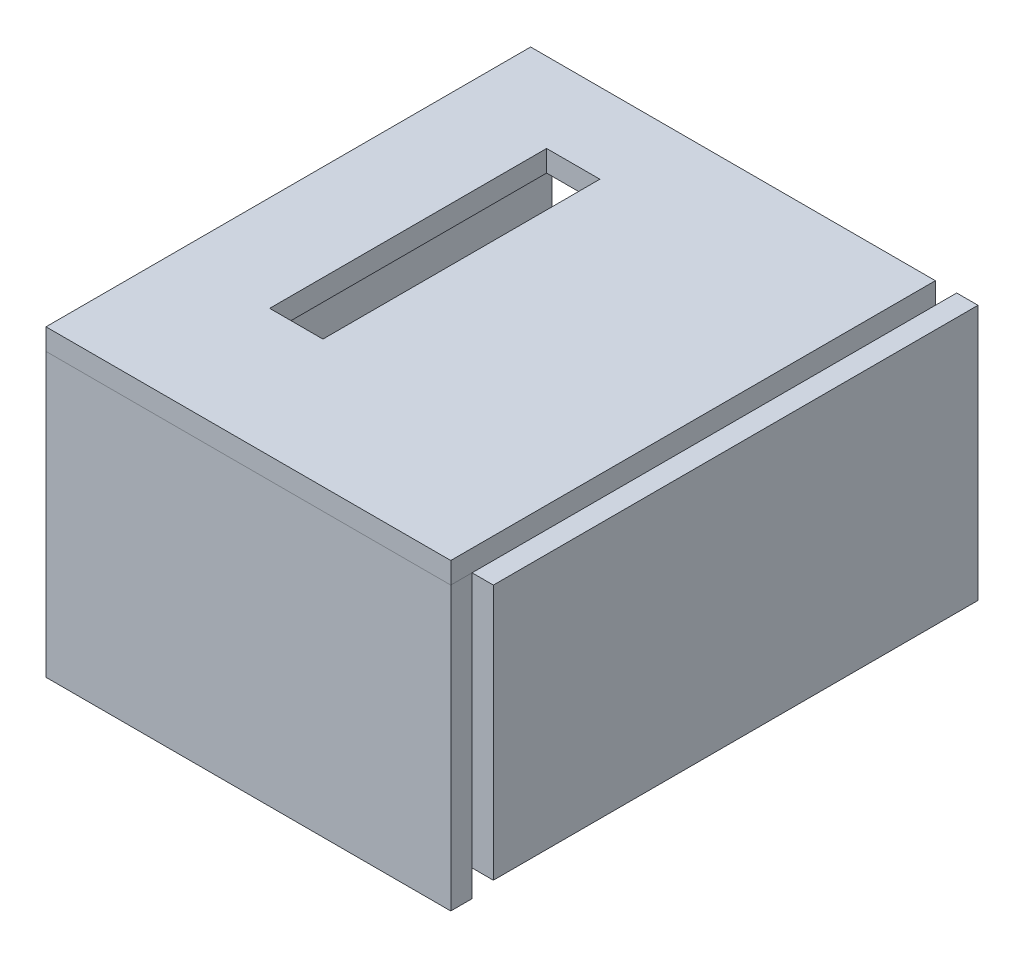
SolidWorks part; units mm, degrees
ref_plane "Front Plane" through (0, 0, 0) normal (0, 0, 1) x (1, 0, 0)
ref_plane "Top Plane" through (0, 0, 0) normal (0, 1, 0) x (1, 0, 0)
ref_plane "Right Plane" through (0, 0, 0) normal (1, 0, 0) x (0, 0, -1)
sketch "Sketch1" plane through (0, 0, 0) normal (0, 1, 0) x (1, 0, 0)
  line L0 (-120.65, -144.4625) -> (-120.65, -68.2625) construction
  line L1 (-120.65, 144.4625) -> (120.65, 144.4625)
  line L2 (-120.65, 144.4625) -> (-120.65, -144.4625)
  line L3 (-120.65, -144.4625) -> (120.65, -144.4625)
  line L4 (120.65, 144.4625) -> (120.65, -144.4625)
  line L5 (-120.65, 144.4625) -> (120.65, -144.4625) construction
  line L6 (-120.65, -144.4625) -> (120.65, 144.4625) construction
  line L7 (-120.65, -68.2625) -> (-63.5, -68.2625) construction
  line L8 (-63.5, -68.2625) -> (-31.75, -68.2625)
  line L9 (-63.5, -68.2625) -> (-63.5, 96.8375)
  line L10 (-63.5, 96.8375) -> (-31.75, 96.8375)
  line L11 (-31.75, 96.8375) -> (-31.75, -68.2625)
  point P0 (0, 0)
  dimension "D1" = 288.925
  dimension "D2" = 241.3
  dimension "D3" = 76.2
  dimension "D4" = 57.15
  dimension "D5" = 31.75
  dimension "D6" = 165.1
extrude "Boss-Extrude1" add sketch "Sketch1" along normal blind 12.7
sketch "Sketch2" plane through (0, 0, 144.4625) normal (0, 0, 1) x (1, 0, 0)
  line L0 (-120.65, 0) -> (120.65, 0)
  line L1 (-120.65, 0) -> (-120.65, -168.275)
  line L2 (120.65, 0) -> (120.65, -168.275)
  line L3 (-120.65, -168.275) -> (120.65, -168.275)
  dimension "D1" = 168.275
extrude "Boss-Extrude3" add sketch "Sketch2" against normal blind 12.7 separate body
sketch "Sketch3" plane through (120.65, 0, 0) normal (1, 0, 0) x (0, 0, -1)
  line L0 (-131.7625, 0) -> (157.1625, 0)
  line L1 (-131.7625, 0) -> (-131.7625, -152.4)
  line L2 (157.1625, 0) -> (157.1625, -152.4)
  line L3 (-131.7625, -152.4) -> (157.1625, -152.4)
  line L4 (-131.7625, -168.275) -> (-131.7625, 0) construction
  point P0 (157.8206, 0)
  dimension "D1" = 152.4
  dimension "D2" = 288.925
extrude "Boss-Extrude4" add sketch "Sketch3" along normal blind 12.7 separate body
sketch "Sketch5" plane through (-120.65, 0, 0) normal (-1, 0, 0) x (0, 0, 1)
  line L0 (-157.1625, 0) -> (131.7625, 0)
  line L1 (-157.1625, 0) -> (-157.1625, -152.4)
  line L2 (131.7625, 0) -> (131.7625, -152.4)
  line L3 (-157.1625, -152.4) -> (131.7625, -152.4)
  point P0 (131.7625, 0)
  dimension "D1" = 152.4
  dimension "D2" = 152.4
  dimension "D3" = 288.925
extrude "Boss-Extrude6" add sketch "Sketch5" along normal blind 12.7 separate body
